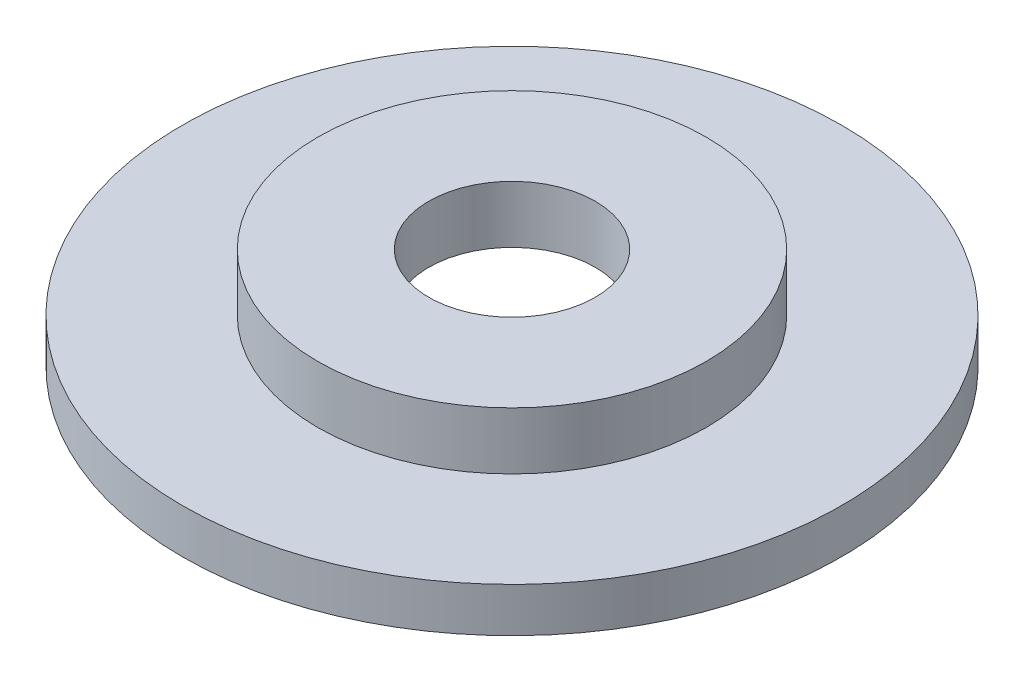
SolidWorks part; units mm, degrees
ref_plane "Front Plane" through (0, 0, 0) normal (0, 0, 1) x (1, 0, 0)
ref_plane "Top Plane" through (0, 0, 0) normal (0, 1, 0) x (1, 0, 0)
ref_plane "Right Plane" through (0, 0, 0) normal (1, 0, 0) x (0, 0, -1)
sketch "Sketch1" plane through (0, 0, 0) normal (0, 0, 1) x (1, 0, 0)
  line L0 (0, 0) -> (0, 8.8) construction
  line L1 (-4.435, 0) -> (-4.435, 1.28)
  line L2 (-4.435, 1.28) -> (-2.4, 1.28)
  line L3 (-2.4, 1.28) -> (-2.4, 2.93)
  line L4 (-2.4, 2.93) -> (-5.6, 2.93)
  line L5 (-5.6, 2.93) -> (-5.6, 1.28)
  line L6 (-5.6, 1.28) -> (-9.5, 1.28)
  line L7 (-9.5, 1.28) -> (-9.5, 0)
  line L8 (-9.5, 0) -> (-4.435, 0)
  dimension "D1" = 4.8
  dimension "D2" = 1.65
  dimension "D3" = 1.28
  dimension "D4" = 8.87
  dimension "D5" = 11.2
  dimension "D6" = 19
revolve "Revolve1" add sketch "Sketch1" angle 360 about L0
